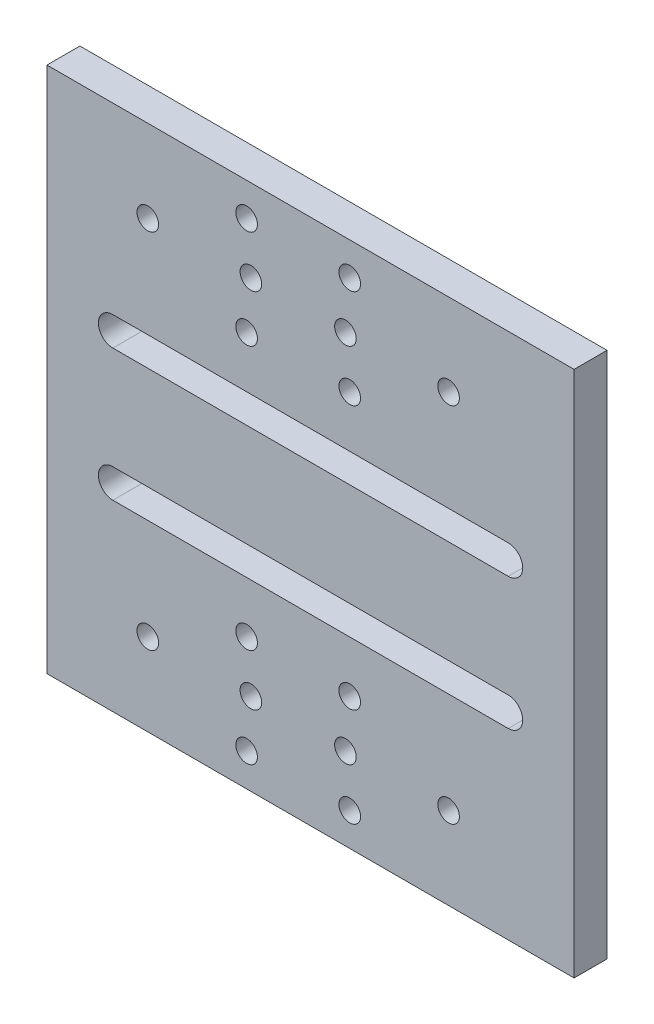
SolidWorks part; units mm, degrees
material "6061 Alloy"
ref_plane "Front Plane" through (0, 0, 0) normal (0, 0, 1) x (1, 0, 0)
ref_plane "Top Plane" through (0, 0, 0) normal (0, 1, 0) x (1, 0, 0)
ref_plane "Right Plane" through (0, 0, 0) normal (1, 0, 0) x (0, 0, -1)
sketch "Sketch1" plane through (0, 0, 0) normal (0, 1, 0) x (1, 0, 0)
  line L1 (0, 0) -> (101.6, 0)
  line L2 (0, 0) -> (0, 6.35)
  line L3 (0, 6.35) -> (101.6, 6.35)
  line L4 (101.6, 0) -> (101.6, 6.35)
  dimension "D1" = 101.6
  dimension "D2" = 6.35
extrude "Boss-Extrude1" add sketch "Sketch1" along normal blind 101.6
sketch "Sketch2" plane through (0, 0, -6.35) normal (0, 0, -1) x (-1, 0, 0)
  line L0 (-88.9, 66.294) -> (-12.7, 66.294)
  line L1 (-88.9, 60.706) -> (-12.7, 60.706)
  line L2 (-101.6, 0) -> (0, 0) construction
  line L3 (-91.694, 63.5) -> (-9.906, 63.5) construction
  line L4 (-101.6, 50.8) -> (0, 50.8) construction
  line L5 (-101.6, 101.6) -> (-101.6, 0) construction
  line L6 (0, 101.6) -> (0, 0) construction
  line L9 (-88.9, 40.894) -> (-12.7, 40.894)
  line L10 (-88.9, 35.306) -> (-12.7, 35.306)
  arc A0 (-12.7, 66.294) -> (-12.7, 60.706) centre (-12.7, 63.5) cw
  arc A1 (-88.9, 66.294) -> (-88.9, 60.706) centre (-88.9, 63.5) ccw
  arc A2 (-12.7, 35.306) -> (-12.7, 40.894) centre (-12.7, 38.1) ccw
  arc A3 (-88.9, 35.306) -> (-88.9, 40.894) centre (-88.9, 38.1) cw
  point P8 (-50.8, 0)
  point P9 (-50.8, 60.706)
  dimension "D1" = 5.588
  dimension "D2" = 76.2
  dimension "D3" = 63.5
extrude "Cut-Extrude1" cut sketch "Sketch2" against normal through all
sketch "Sketch5" plane through (0, 0, 0) normal (0, 0, 1) x (1, 0, 0)
  line L2 (38.481, 76.2) -> (38.481, 95.25) construction
  line L3 (19.431, 85.725) -> (57.531, 85.725) construction
  line L4 (0, 101.6) -> (0, 0) construction
  line L5 (0, 101.6) -> (101.6, 101.6) construction
  circle A0 centre (19.431, 85.725) radius 2.0828
  circle A1 centre (38.481, 95.25) radius 2.0828
  circle A2 centre (38.481, 76.2) radius 2.0828
  circle A4 centre (57.531, 85.725) radius 2.0828
  point P5 (38.481, 85.725)
  point P6 (38.481, 85.725)
  dimension "D3" = 4.1656
  dimension "D1" = 19.05
  dimension "D2" = 38.1
  dimension "D4" = 38.481
  dimension "D5" = 15.875
extrude "Cut-Extrude2" cut sketch "Sketch5" against normal through all
ref_plane "Plane1" through (0, 50.8, 0) normal (0, 1, 0) x (1, 0, 0)
ref_plane "Plane2" through (48.4187, 0, 0) normal (1, 0, 0) x (0, 0, -1)
mirror "Mirror1" about plane through (0, 50.8, 0) normal (0, 1, 0) of "Cut-Extrude2"
mirror "Mirror2" about plane through (48.4187, 0, 0) normal (1, 0, 0) of "Mirror1", "Cut-Extrude2"
